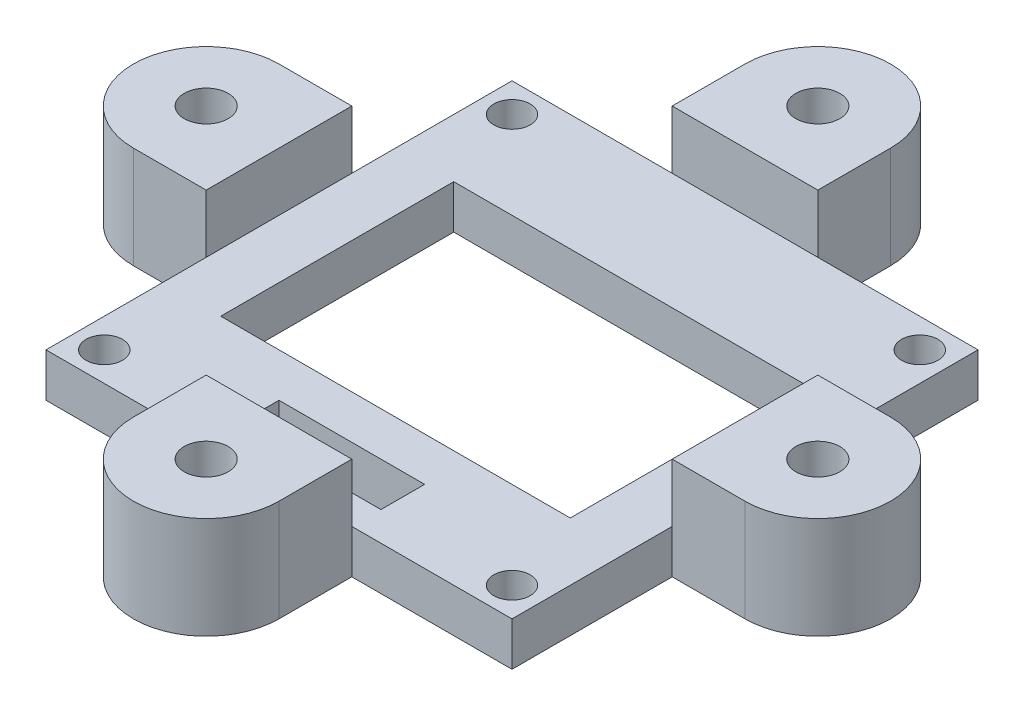
SolidWorks part; units mm, degrees
ref_plane "前视基准面" through (0, 0, 0) normal (0, 0, 1) x (1, 0, 0)
ref_plane "上视基准面" through (0, 0, 0) normal (0, 1, 0) x (1, 0, 0)
ref_plane "右视基准面" through (0, 0, 0) normal (1, 0, 0) x (0, 0, -1)
sketch "草图2" plane through (0, 0, 0) normal (0, 1, 0) x (1, 0, 0)
  line L1 (-12, 0) -> (-12, 8)
  line L2 (21, 5) -> (16, 5)
  line L4 (21, -5) -> (16, -5)
  line L9 (12, 0) -> (12, 8)
  line L10 (12, 8) -> (-12, 8)
  line L11 (12, 0) -> (12, -8)
  line L12 (-12, 0) -> (-12, -8)
  line L13 (-12, -8) -> (12, -8)
  line L14 (0, -11) -> (5, -11)
  line L15 (0, -11) -> (-5, -11)
  line L16 (0, -14) -> (-5, -14)
  line L17 (-5, -14) -> (-5, -11)
  line L18 (0, -14) -> (5, -14)
  line L19 (5, -14) -> (5, -11)
  line L24 (16, -5) -> (16, -16)
  line L25 (16, 5) -> (16, 16)
  line L27 (5, 16) -> (16, 16)
  line L30 (-5, 16) -> (-16, 16)
  line L35 (-16, 5) -> (-16, 16)
  line L37 (-16, -5) -> (-16, -16)
  line L39 (-5, -16) -> (-16, -16)
  line L41 (5, -16) -> (16, -16)
  line L42 (-5, -16) -> (-5, -21)
  line L43 (5, -16) -> (5, -21)
  line L44 (-21, 5) -> (-16, 5)
  line L45 (-21, -5) -> (-16, -5)
  line L46 (-5, 16) -> (-5, 21)
  line L47 (5, 21) -> (5, 16)
  circle A0 centre (-14, 14) radius 1.25
  circle A1 centre (14, 14) radius 1.25
  circle A2 centre (14, -14) radius 1.25
  circle A3 centre (-14, -14) radius 1.25
  circle A4 centre (21, 0) radius 1.51
  circle A5 centre (0, 21) radius 1.51
  circle A6 centre (0, -21) radius 1.51
  circle A7 centre (-21, 0) radius 1.51
  arc A8 (21, -5) -> (21, 5) centre (21, 0) ccw
  arc A9 (5, -21) -> (-5, -21) centre (0, -21) cw
  arc A10 (-21, 5) -> (-21, -5) centre (-21, 0) ccw
  arc A11 (-5, 21) -> (5, 21) centre (0, 21) cw
extrude "凸台-拉伸1" add sketch "草图2" along normal blind 3 contours L12 L13 L11 L9 L10 L1 | L18 L19 L14 L15 L17 L16 | A3 | A7 | A5 | A1 | A4 | A2 | A6 | L47 L27 L25 L2 A8 L4 L24 L41 L43 A9 L42 L39 L37 L45 A10 L44 L35 L30 L46 A11 | A0
sketch "草图4" plane through (0, 3, 0) normal (0, 1, 0) x (1, 0, 0)
  line L0 (-16, -5) -> (-16, 5)
  line L1 (-16, 5) -> (-21, 5)
  line L2 (-21, -5) -> (-16, -5)
  arc A0 (-21, 5) -> (-21, -5) centre (-21, 0) ccw
  arc A1 (-21, 5) -> (-21, -5) centre (-21, 0) ccw construction
  line M13 (-16, 5) -> (-21, 5)
  arc M14 (-21, 5) -> (-21, -5) centre (-21, 0) ccw
  line M15 (-21, -5) -> (-16, -5)
  circle M34 centre (-21, 0) radius 1.51
extrude "凸台-拉伸2" add sketch "草图4" along normal blind 4.5 contours L0 M15 M13 M14 M34
sketch "草图5" plane through (0, 3, 0) normal (0, 1, 0) x (1, 0, 0)
  line L0 (-5, -21) -> (-5, -16)
  line L1 (-5, -16) -> (5, -16)
  line L2 (5, -16) -> (5, -21)
  line L3 (21, -5) -> (16, -5)
  line L4 (16, -5) -> (16, 5)
  line L5 (16, 5) -> (21, 5)
  line L6 (-5, 21) -> (-5, 16)
  line L7 (-5, 16) -> (5, 16)
  line L8 (5, 16) -> (5, 21)
  arc A0 (5, -21) -> (-5, -21) centre (0, -21) cw
  arc A1 (21, -5) -> (21, 5) centre (21, 0) ccw construction
  arc A2 (21, -5) -> (21, 5) centre (21, 0) ccw
  circle A3 centre (21, 0) radius 1.51
  circle A4 centre (0, -21) radius 1.51
  arc A5 (-5, 21) -> (5, 21) centre (0, 21) cw
  circle A6 centre (0, 21) radius 1.51
  circle M2 centre (0, -21) radius 1.51
  circle M4 centre (21, 0) radius 1.51
  circle M6 centre (0, 21) radius 1.51
  line M19 (-5, -16) -> (-5, -21)
  arc M20 (-5, -21) -> (5, -21) centre (0, -21) ccw
  line M21 (5, -21) -> (5, -16)
  line M24 (16, -5) -> (21, -5)
  arc M25 (21, -5) -> (21, 5) centre (21, 0) ccw
  line M26 (21, 5) -> (16, 5)
  line M29 (5, 16) -> (5, 21)
  arc M30 (5, 21) -> (-5, 21) centre (0, 21) ccw
  line M31 (-5, 21) -> (-5, 16)
extrude "凸台-拉伸3" add sketch "草图5" along normal blind 4.5 contours L7 M31 M29 M30 M6 | L4 M24 M25 M26 M4 | L1 M19 M20 M21 M2
sketch "草图7" plane through (0, 7.5, 0) normal (0, 1, 0) x (1, 0, 0)
  line L1 (-42.7172, -33.2572) -> (51.2959, -33.2572)
  line L2 (-42.7172, -33.2572) -> (-42.7172, 32.6696)
  line L3 (-42.7172, 32.6696) -> (51.2959, 32.6696)
  line L4 (51.2959, -33.2572) -> (51.2959, 32.6696)
extrude "切除-拉伸1" cut sketch "草图7" against normal blind 0.5
